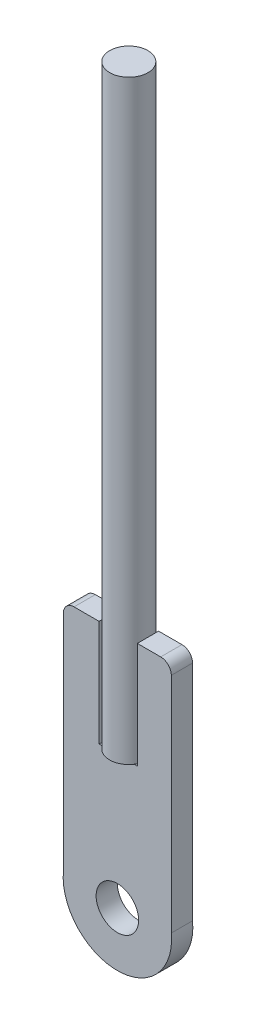
SolidWorks part; units mm, degrees
ref_plane "Front Plane" through (0, 0, 0) normal (0, 0, 1) x (1, 0, 0)
ref_plane "Top Plane" through (0, 0, 0) normal (0, 1, 0) x (1, 0, 0)
ref_plane "Right Plane" through (0, 0, 0) normal (1, 0, 0) x (0, 0, -1)
sketch "Sketch1" plane through (0, 0, 0) normal (0, 1, 0) x (1, 0, 0)
  circle A0 centre (0, 0) radius 9
  dimension "D1" = 18
extrude "Boss-Extrude1" add sketch "Sketch1" along normal blind 280
sketch "Sketch2" plane through (0, 0, 0) normal (0, 0, 1) x (1, 0, 0)
  line L0 (20, 50) -> (9, 50)
  line L2 (25, 45) -> (25, -60)
  line L3 (-25.7631, 45) -> (-25.7631, -60)
  line L5 (9, 0) -> (-9, 0)
  line L6 (-9, 0) -> (-9, 50)
  line L7 (-9, 280) -> (-9, 0) construction
  line L8 (9, 0) -> (9, 50)
  line L9 (9, 0) -> (9, 280) construction
  line L11 (-9, 50) -> (-20.7631, 50)
  arc A0 (25, -60) -> (-25.7631, -60) centre (-0.3815, -62.5) cw
  circle A3 centre (-0.3815, -62.5) radius 10
  arc A4 (-25.7631, 45) -> (-20.7631, 50) centre (-20.7631, 45) cw
  arc A5 (25, 45) -> (20, 50) centre (20, 45) ccw
  point P0 (0, 0)
  dimension "D5" = 20
  dimension "D2" = 5
  dimension "D1" = 50
extrude "Boss-Extrude2" add sketch "Sketch2" along normal mid plane 10 separate body
